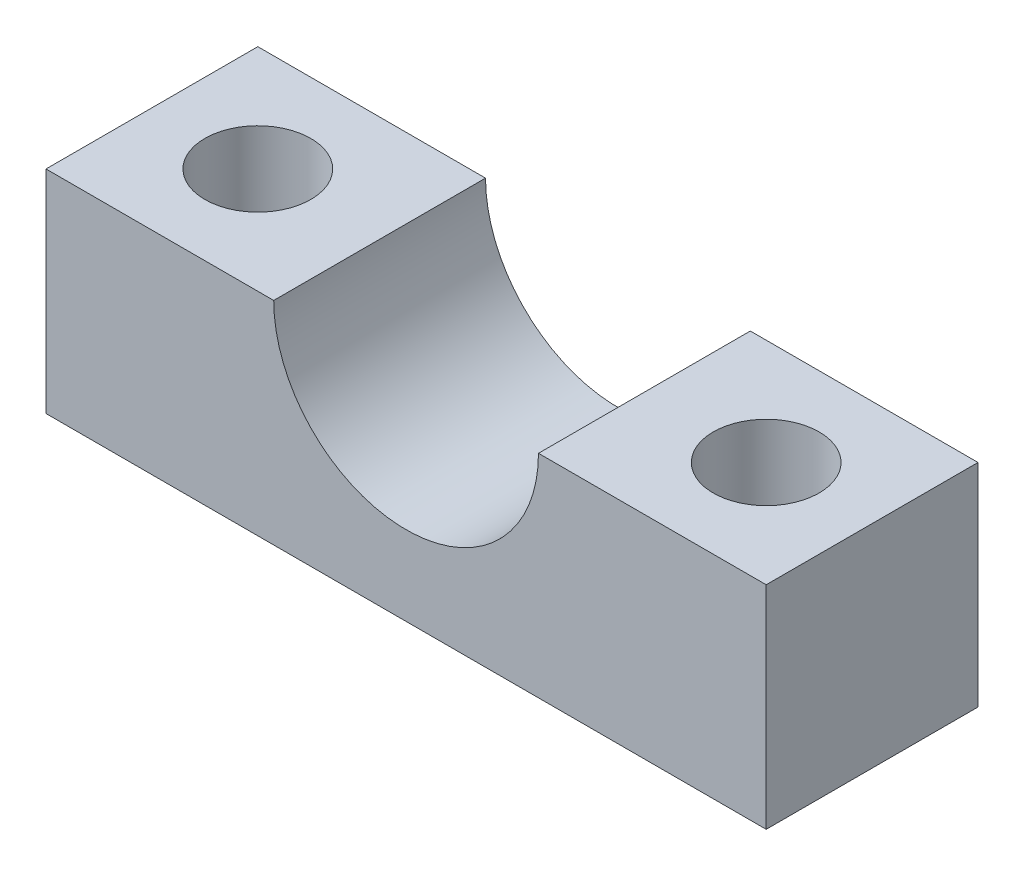
SolidWorks part; units mm, degrees
material "6061 Alloy"
ref_plane "Front Plane" through (0, 0, 0) normal (0, 0, 1) x (1, 0, 0)
ref_plane "Top Plane" through (0, 0, 0) normal (0, 1, 0) x (1, 0, 0)
ref_plane "Right Plane" through (0, 0, 0) normal (1, 0, 0) x (0, 0, -1)
sketch "Sketch2" plane through (0, 0, 0) normal (0, 1, 0) x (1, 0, 0)
  line L0 (0, 6.35) -> (0, -6.35) construction
  line L1 (21.59, -6.35) -> (-21.59, -6.35)
  line L2 (21.59, -6.35) -> (21.59, 6.35)
  line L3 (21.59, 6.35) -> (-21.59, 6.35)
  line L4 (-21.59, -6.35) -> (-21.59, 6.35)
  line L5 (21.59, -6.35) -> (-21.59, 6.35) construction
  line L6 (21.59, 6.35) -> (-21.59, -6.35) construction
  circle A0 centre (-15.24, 0) radius 3.175
  circle A1 centre (15.24, 0) radius 3.175
  point P0 (0, 0)
  dimension "D1" = 6.35
  dimension "D2" = 6.35
  dimension "D3" = 12.7
  dimension "D4" = 15.24
extrude "Boss-Extrude1" add sketch "Sketch2" along normal blind 12.7
sketch "Sketch3" plane through (0, 0, 6.35) normal (0, 0, 1) x (1, 0, 0)
  line L0 (-21.59, 12.7) -> (21.59, 12.7) construction
  circle A0 centre (0, 12.7) radius 7.9375
  dimension "D1" = 15.875
extrude "Cut-Extrude1" cut sketch "Sketch3" against normal through all
